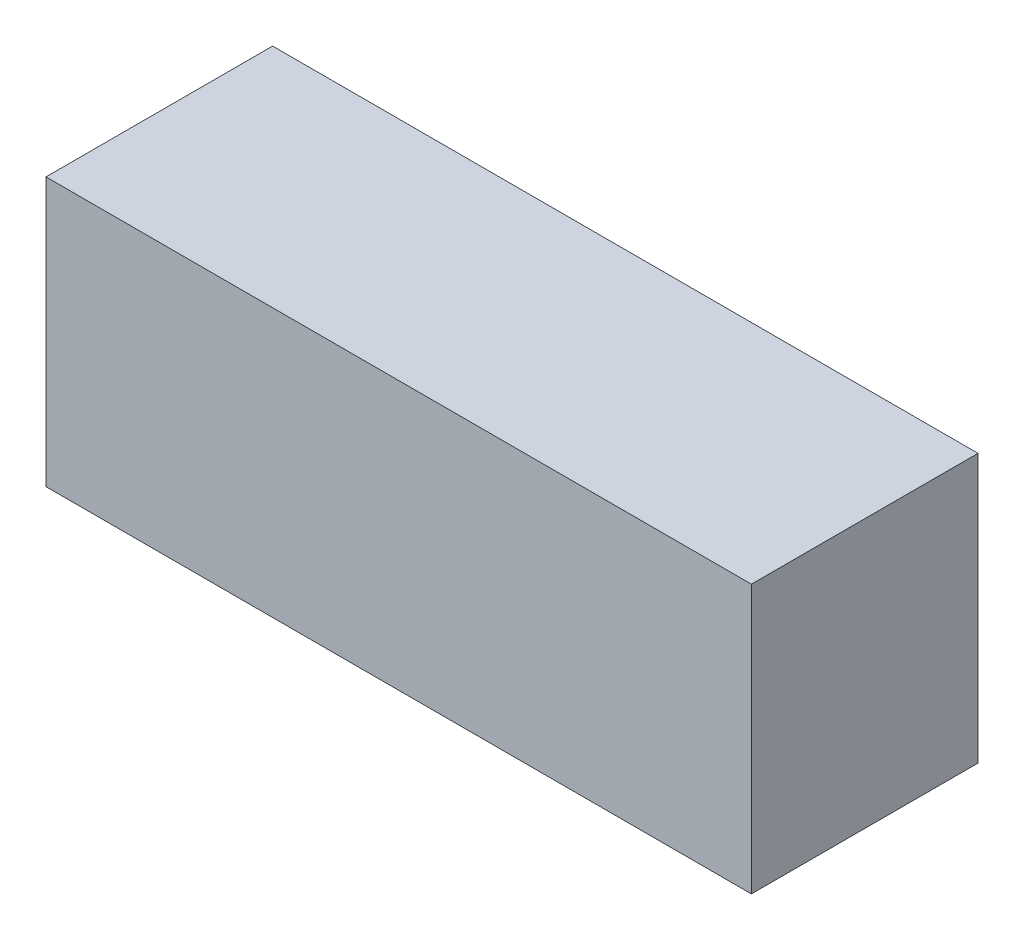
SolidWorks part; units mm, degrees
ref_plane "Front Plane" through (0, 0, 0) normal (0, 0, 1) x (1, 0, 0)
ref_plane "Top Plane" through (0, 0, 0) normal (0, 1, 0) x (1, 0, 0)
ref_plane "Right Plane" through (0, 0, 0) normal (1, 0, 0) x (0, 0, -1)
sketch "Sketch1" plane through (0, 0, 0) normal (0, 0, 1) x (1, 0, 0)
  line L0 (-1.37, -1.534) -> (6.5369, -1.534)
  line L1 (6.5369, -1.534) -> (6.5369, 1.4732)
  line L2 (6.5369, 1.4732) -> (-1.37, 1.4732)
  line L3 (-1.37, 1.4732) -> (-1.37, -1.534)
extrude "Component_Outline" add sketch "Sketch1" along normal blind 2.54 separate body
sketch3d "3DSketch1"
  line L0 (0, 0, 0) -> (1, 0, 0)
  line L1 (0, 0, 0) -> (0, 1, 0)
  line L2 (0, 0, 0) -> (0, 0, 1)
  point P0 (0, 0, 0)
